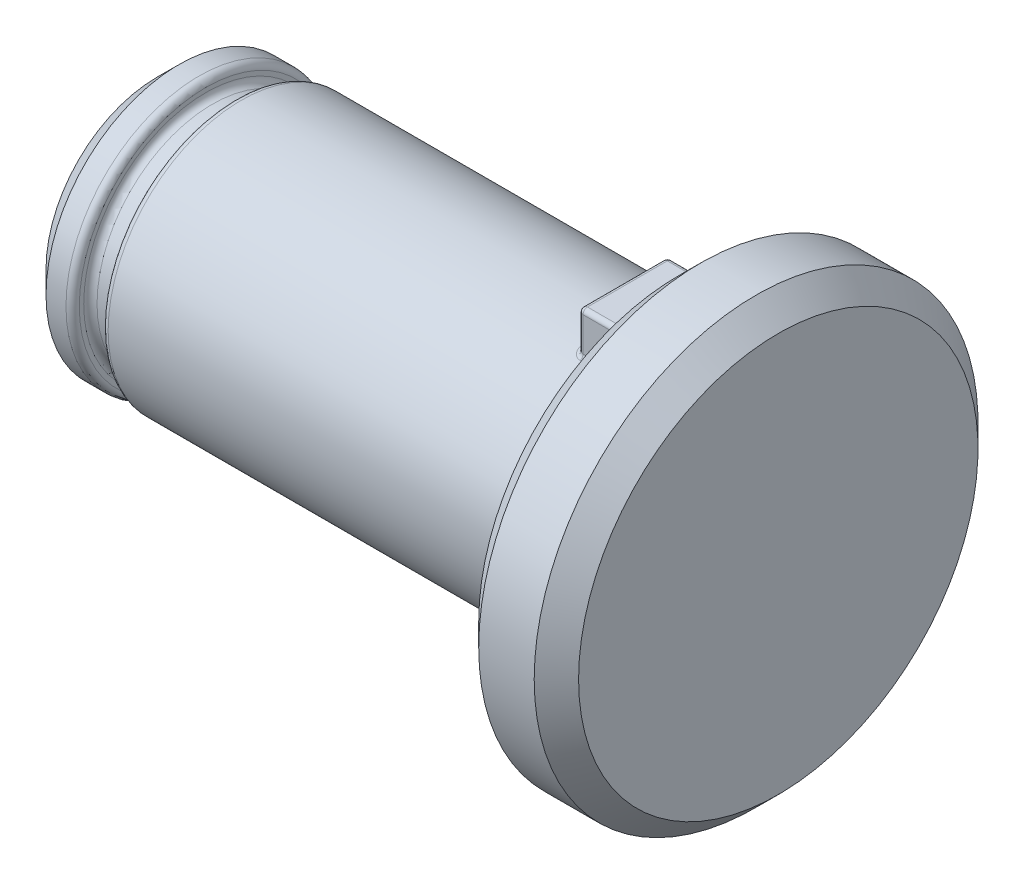
SolidWorks part; units mm, degrees
material "ABS"
ref_plane "Front Plane" through (0, 0, 0) normal (1, 0, 0) x (0, 1, 0)
ref_plane "Top Plane" through (0, 0, 0) normal (0, 0, 1) x (0, 1, 0)
ref_plane "Right Plane" through (0, 0, 0) normal (0, 1, 0) x (-1, 0, 0)
sketch "Sketch1" plane through (0, 0, 0) normal (0, 1, 0) x (-1, 0, 0)
  line L0 (0, 0) -> (0, 10) construction
  line L1 (-1, 10) -> (-3.5, 10)
  line L2 (-4.5, 9) -> (-4.5, 0)
  line L3 (-4.5, 0) -> (23.5, 0) construction
  line L4 (23.5, 0) -> (23.5, 5)
  line L5 (22.5, 6) -> (21.6, 6)
  line L6 (0, 9) -> (0, 8)
  line L7 (21.3, 5.7) -> (21.3, 5.5)
  line L8 (21, 5.2) -> (20.3, 5.2)
  line L9 (20, 5.5) -> (20, 5.7)
  line L10 (19.7, 6) -> (2, 6)
  line L11 (23.5, 5) -> (22.5, 6)
  line L12 (-1, 10) -> (0, 9)
  line L13 (-3.5, 10) -> (-4.5, 9)
  line L14 (23.5, 0) -> (-4.5, 0)
  arc A0 (2, 6) -> (0, 8) centre (2, 8) cw
  arc A1 (21.3, 5.7) -> (21.6, 6) centre (21.6, 5.7) cw
  arc A2 (21.3, 5.5) -> (21, 5.2) centre (21, 5.5) cw
  arc A3 (20.3, 5.2) -> (20, 5.5) centre (20.3, 5.5) cw
  arc A4 (20, 5.7) -> (19.7, 6) centre (19.7, 5.7) ccw
  point P4 (-4.5, 10)
  point P7 (23.5, 6)
  point P20 (0, 6)
  point P25 (21.3, 5.2)
  point P28 (20, 5.2)
  point P31 (20, 6)
  dimension "D8" = 2
  dimension "D9" = 0.3
  dimension "D1" = 12
  dimension "D2" = 20
  dimension "D3" = 4.5
  dimension "D4" = 3.5
  dimension "D5" = 0.8
  dimension "D6" = 20
  dimension "D7" = 1.3
revolve "Revolve1" add sketch "Sketch1" angle 360 about L14
sketch "Sketch2" plane through (0, 0, 0) normal (-1, 0, 0) x (0, -1, 0)
  line L0 (5.6569, 2) -> (7.5319, 2)
  line L1 (7.5319, 2) -> (7.5319, -2)
  line L2 (7.5319, -2) -> (5.6569, -2)
  line L3 (-5.6569, -2) -> (-7.5319, -2)
  line L4 (-7.5319, -2) -> (-7.5319, 2)
  line L5 (-7.5319, 2) -> (-5.6569, 2)
  line L6 (-7.5319, 0) -> (0, 0) construction
  line L7 (0, 0) -> (7.5319, 0) construction
  circle A0 centre (0, 0) radius 6 construction
  arc A1 (5.6569, -2) -> (5.6569, 2) centre (0, 0) ccw
  circle A2 centre (0, 0) radius 6 construction
  arc A3 (-5.6569, 2) -> (-5.6569, -2) centre (0, 0) ccw
  dimension "D1" = 4
  dimension "D2" = 1.875
extrude "Boss-Extrude1" add sketch "Sketch2" along normal blind 2.5
fillet "Fillet1" radius 0.2 22 edges at (-2.5, 6, 0) (-0.0408, -7.5319, -1.0002) (-2.25, -5.6569, 2) (-2.25, -5.6569, -2) (-2.25, 5.6569, -2) (-2.25, 5.6569, 2) (-3.3005, -9.307, 2) (-3.6203, -8.9517, -2) (-2.5, -6, 0) (-3.3005, 9.307, -2) (-3.6203, 8.9517, 2) (-0.0408, 7.5319, 1.0002) (-1.2554, -7.5319, 2) (-1.2554, 7.5319, 2) (-2.5, 6.5944, 2) (-2.5, 7.5319, 0) (-2.5, 6.5944, -2) (-1.2554, 7.5319, -2) (-1.2554, -7.5319, -2) (-2.5, -6.5944, 2) (-2.5, -6.5944, -2) (-2.5, -7.5319, 0)
sketch "Sketch3" plane through (-23.5, 0, 0) normal (-1, 0, 0) x (0, -1, 0)
  circle A0 centre (0, 0) radius 3.1
  dimension "D1" = 6.2
extrude "Cut-Extrude1" cut sketch "Sketch3" against normal blind 2.5
fillet "Fillet2" radius 0.1 2 edges at (-21, 0, 3.1) (-23.5, 0, 3.1)
